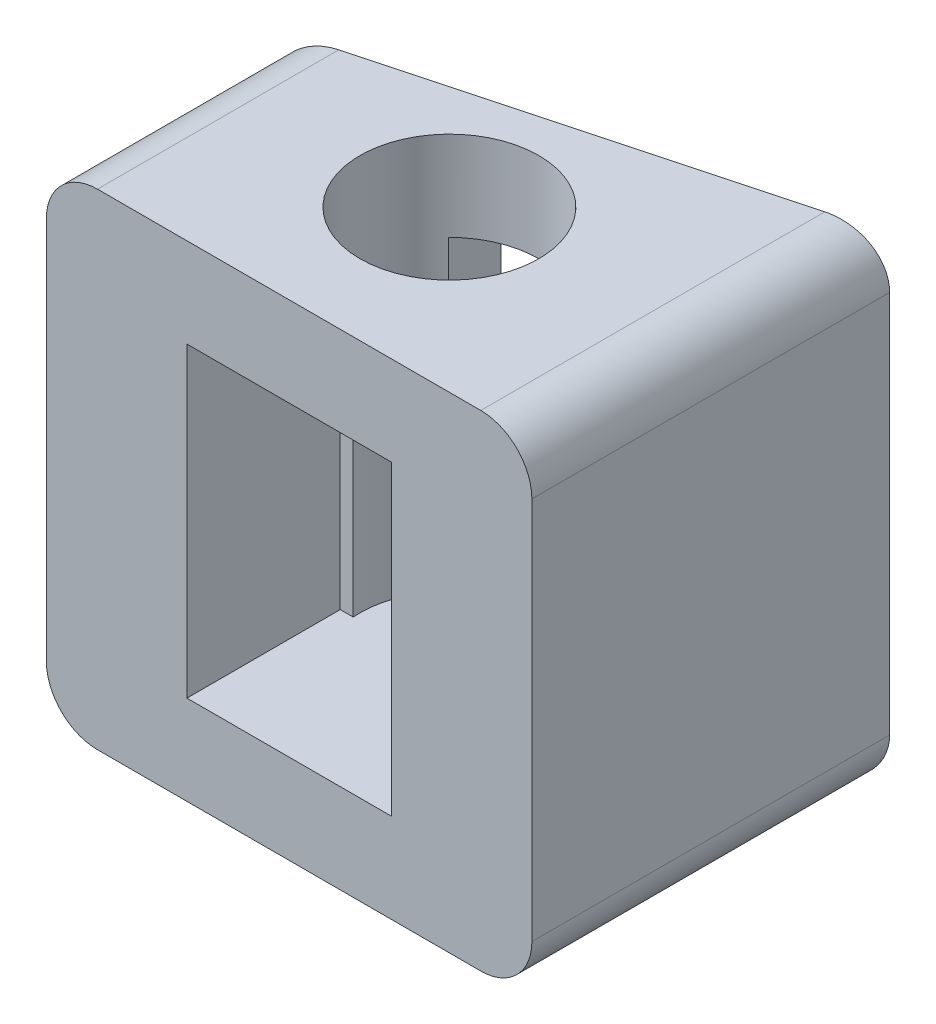
SolidWorks part; units mm, degrees
ref_plane "Front" through (0, 0, 0) normal (0, 0, 1) x (1, 0, 0)
ref_plane "Top" through (0, 0, 0) normal (0, 1, 0) x (1, 0, 0)
ref_plane "Right" through (0, 0, 0) normal (1, 0, 0) x (0, 0, -1)
sketch "Sketch1" plane through (0, 0, 0) normal (0, 0, 1) x (1, 0, 0)
  line L1 (-3.75, 4.75) -> (3.75, 4.75)
  line L2 (-4.75, 3.75) -> (-4.75, -3.75)
  line L3 (-3.75, -4.75) -> (3.75, -4.75)
  line L4 (4.75, 3.75) -> (4.75, -3.75)
  line L5 (-4.75, 4.75) -> (4.75, -4.75) construction
  line L6 (-4.75, -4.75) -> (4.75, 4.75) construction
  arc A0 (3.75, 4.75) -> (4.75, 3.75) centre (3.75, 3.75) cw
  arc A1 (4.75, -3.75) -> (3.75, -4.75) centre (3.75, -3.75) cw
  arc A2 (-3.75, -4.75) -> (-4.75, -3.75) centre (-3.75, -3.75) cw
  arc A3 (-3.75, 4.75) -> (-4.75, 3.75) centre (-3.75, 3.75) ccw
  point P0 (0, 0)
  point P5 (0, 0)
  dimension "D3" = 1
  dimension "D1" = 9.5
  dimension "D2" = 9.5
extrude "Boss-Extrude1" add sketch "Sketch1" along normal blind 10
sketch "Sketch2" plane through (0, 0, 0) normal (0, 1, 0) x (1, 0, 0)
  line L0 (4.75, 0) -> (-4.75, 0)
  line L1 (-3.75, 0) -> (-4.75, 0) construction
  line L2 (-4.75, 0) -> (-4.75, -2.5455)
  line L3 (-4.75, -2.5455) -> (4.75, 0)
  line L4 (-4.75, -10) -> (-4.75, 0) construction
  dimension "D1" = 15
extrude "Cut-Extrude1" cut sketch "Sketch2" against normal mid plane 10
sketch "Sketch11" plane through (0, 4.75, 0) normal (0, 1, 0) x (1, 0, 0)
  line L0 (4.75, -10) -> (4.75, 0) construction
  line L1 (-4.75, -10) -> (4.75, -10)
  line L2 (-4.75, -10) -> (-4.75, -7)
  line L3 (-4.75, -7) -> (4.75, -7)
  line L4 (4.75, -10) -> (4.75, -7)
  dimension "D1" = 7
extrude "Cut-Extrude9" cut sketch "Sketch11" against normal through all
ref_plane "Plane2" through (2.1299, 0, 7.949) normal (-0.2588, 0, -0.9659) x (-0.9659, 0, 0.2588)
sketch "Sketch17" plane through (0, 0, 7) normal (0, 0, 1) x (1, 0, 0)
  line L5 (1.25, -3) -> (-1.25, -3)
  line L6 (1.25, -3) -> (1.25, 3)
  line L7 (1.25, 3) -> (-1.25, 3)
  line L8 (-1.25, -3) -> (-1.25, 3)
  line L9 (1.25, -3) -> (-1.25, 3) construction
  line L10 (1.25, 3) -> (-1.25, -3) construction
  point P0 (0, 0)
  dimension "D1" = 6
  dimension "D2" = 2.5
extrude "Cut-Extrude13" cut sketch "Sketch17" against normal through all
sketch "Sketch16" plane through (0, 4.75, 0) normal (0, 1, 0) x (1, 0, 0)
  line L0 (3.75, -0.2679) -> (-3.75, -2.2776) construction
  circle A0 centre (-0.0022, -3.8615) radius 1.75
  point P2 (0.6077, -3.4868)
  point P5 (0, -3.3429)
  point P6 (0, -3.8615)
  dimension "D1" = 3.5
  dimension "D2" = 2.5
extrude "Cut-Extrude14" cut sketch "Sketch16" against normal up to surface (7.75 mm away) up to face at (0, -3, 4.1364)
sketch "Sketch18" plane through (0, 0, 7) normal (0, 0, 1) x (1, 0, 0)
  line L0 (-1.25, -3) -> (1.25, -3) construction
  line L1 (-2, 3) -> (2, 3)
  line L2 (-2, 3) -> (-2, -3)
  line L3 (-2, -3) -> (2, -3)
  line L4 (2, 3) -> (2, -3)
  line L5 (-2, 3) -> (2, -3) construction
  line L6 (-2, -3) -> (2, 3) construction
  point P0 (0, 0)
  dimension "D1" = 4
extrude "Cut-Extrude15" cut sketch "Sketch18" against normal blind 3
